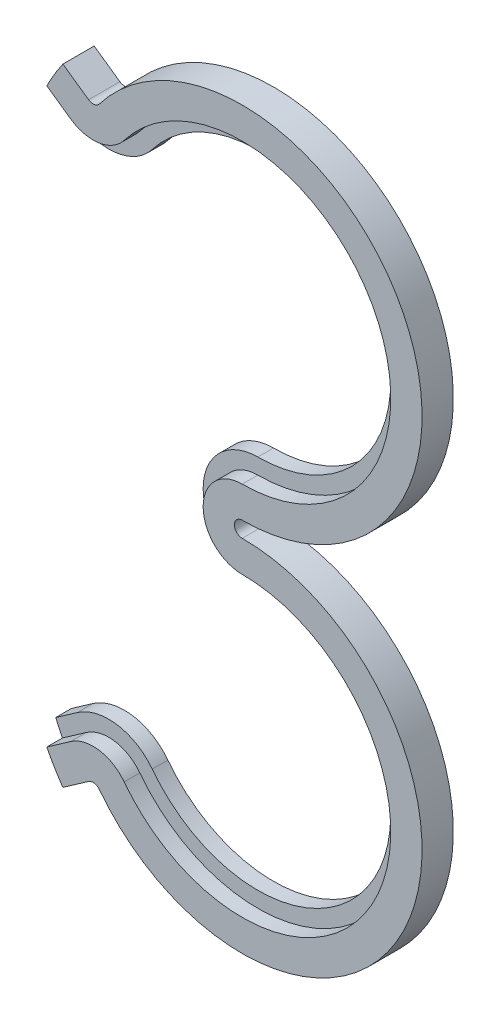
SolidWorks part; units mm, degrees
ref_plane "Plan de face" through (0, 0, 0) normal (0, 0, 1) x (1, 0, 0)
ref_plane "Plan de dessus" through (0, 0, 0) normal (0, 1, 0) x (1, 0, 0)
ref_plane "Plan de droite" through (0, 0, 0) normal (1, 0, 0) x (0, 0, -1)
sketch "Esquisse1" plane through (0, 0, 0) normal (0, 0, 1) x (1, 0, 0)
  line L8 (-12.9225, 17.3861) -> (-11.542, 16.4195)
  line L9 (-11.542, -16.4195) -> (-12.9225, -17.3861)
  line L10 (-11.4681, -20.0301) -> (-9.8213, -18.8769)
  line L11 (-9.8213, 18.8769) -> (-11.4681, 20.0301)
  arc A24 (-11.4681, 20.0301) -> (-12.9225, 17.3861) centre (0, 12) ccw
  arc A25 (-11.542, 16.4195) -> (-6.7536, 17.1613) centre (-9.5345, 19.2865) ccw
  arc A26 (0, 3.5) -> (-6.7536, 17.1613) centre (0, 12) ccw
  arc A27 (0, 3.5) -> (0, -3.5) centre (0, 0) ccw
  arc A28 (-6.7536, -17.1613) -> (0, -3.5) centre (0, -12) ccw
  arc A29 (-6.7536, -17.1613) -> (-11.542, -16.4195) centre (-9.5345, -19.2865) ccw
  arc A30 (-12.9225, -17.3861) -> (-11.4681, -20.0301) centre (0, -12) ccw
  arc A31 (-9.1372, -18.9829) -> (-9.8213, -18.8769) centre (-9.5345, -19.2865) ccw
  arc A32 (-9.1372, -18.9829) -> (0, -0.5) centre (0, -12) ccw
  arc A33 (0, 0.5) -> (0, -0.5) centre (0, 0) ccw
  arc A34 (0, 0.5) -> (-9.1372, 18.9829) centre (0, 12) ccw
  arc A35 (-9.8213, 18.8769) -> (-9.1372, 18.9829) centre (-9.5345, 19.2865) ccw
extrude "Boss.-Extru.2" add sketch "Esquisse1" along normal blind 2
sketch "Esquisse2" plane through (0, 0, 2) normal (0, 0, 1) x (1, 0, 0)
  line L2 (-12.9225, 17.3861) -> (-11.542, 16.4195)
  line L3 (-11.542, -16.4195) -> (-12.9225, -17.3861)
  line L4 (-10.9684, -17.2386) -> (-12.3489, -18.2052)
  line L5 (-12.3489, 18.2052) -> (-10.9684, 17.2386)
  line L6 (-10.9684, -17.2386) -> (-12.3489, -18.2052)
  line L7 (-12.3489, 18.2052) -> (-10.9684, 17.2386)
  line L8 (-12.9225, 17.3861) -> (-13.2956, 18.2052)
  line L9 (-12.3489, 18.2052) -> (-12.8989, 18.5904)
  line L10 (-12.8989, 18.5904) -> (-13.2956, 18.2052)
  line L11 (-12.3489, -18.2052) -> (-12.98, -18.6471)
  line L12 (-12.98, -18.6471) -> (-12.9225, -17.3861)
  arc A11 (-11.542, 16.4195) -> (-6.7536, 17.1613) centre (-9.5345, 19.2865) ccw
  arc A12 (0, 3.5) -> (-6.7536, 17.1613) centre (0, 12) ccw
  arc A13 (0, 3.5) -> (0, -3.5) centre (0, 0) ccw
  arc A14 (-6.7536, -17.1613) -> (0, -3.5) centre (0, -12) ccw
  arc A15 (-6.7536, -17.1613) -> (-11.542, -16.4195) centre (-9.5345, -19.2865) ccw
  arc A16 (-7.5481, -17.7685) -> (0, -2.5) centre (0, -12) ccw
  arc A17 (-7.5481, -17.7685) -> (-10.9684, -17.2386) centre (-9.5345, -19.2865) ccw
  arc A18 (0, 2.5) -> (0, -2.5) centre (0, 0) ccw
  arc A19 (0, 2.5) -> (-7.5481, 17.7685) centre (0, 12) ccw
  arc A20 (-10.9684, 17.2386) -> (-7.5481, 17.7685) centre (-9.5345, 19.2865) ccw
  arc A21 (-7.5481, -17.7685) -> (0, -2.5) centre (0, -12) ccw
  arc A22 (-7.5481, -17.7685) -> (-10.9684, -17.2386) centre (-9.5345, -19.2865) ccw
  arc A23 (0, 2.5) -> (0, -2.5) centre (0, 0) ccw
  arc A24 (0, 2.5) -> (-7.5481, 17.7685) centre (0, 12) ccw
  arc A25 (-10.9684, 17.2386) -> (-7.5481, 17.7685) centre (-9.5345, 19.2865) ccw
  dimension "D1" = 1
  dimension "D2" = 1
extrude "Enlèv. mat.-Extru.1" cut sketch "Esquisse2" against normal blind 1
